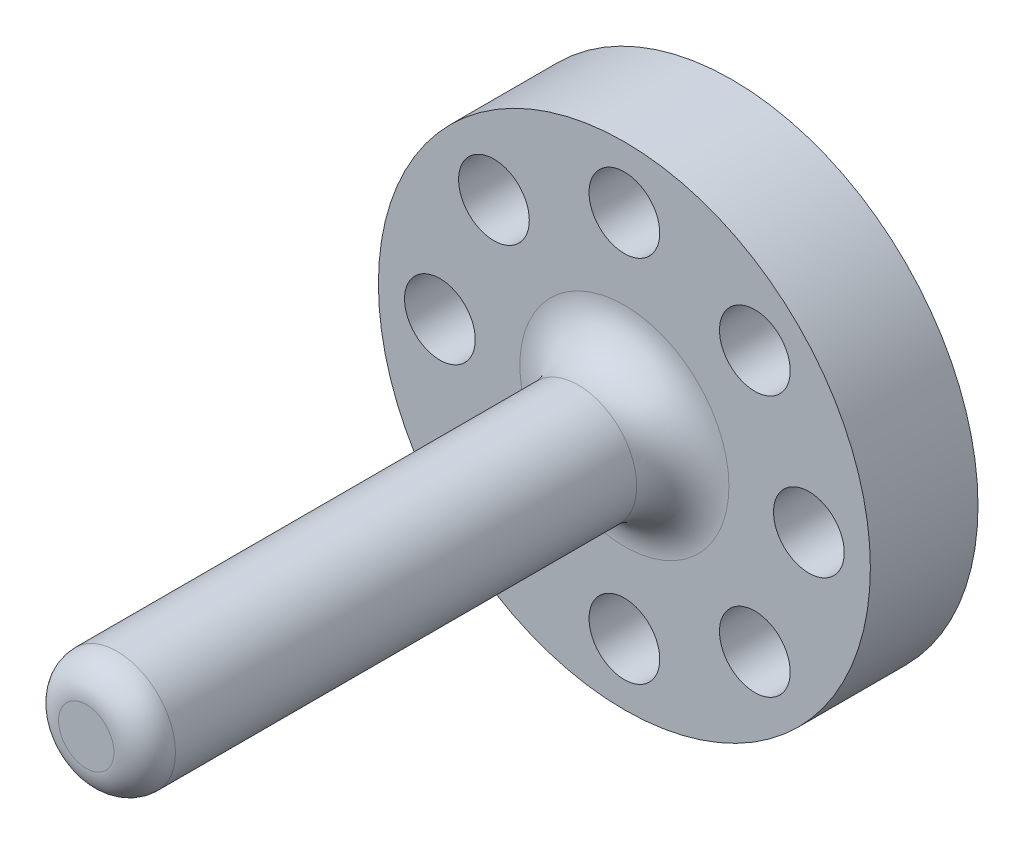
SolidWorks part; units mm, degrees
material "ABS"
ref_plane "正面" through (0, 0, 0) normal (0, 0, 1) x (1, 0, 0)
ref_plane "平面" through (0, 0, 0) normal (0, 1, 0) x (1, 0, 0)
ref_plane "右側面" through (0, 0, 0) normal (1, 0, 0) x (0, 0, -1)
sketch "ｽｹｯﾁ1" plane through (0, 0, 0) normal (0, 0, 1) x (1, 0, 0)
  circle A0 centre (0, 0) radius 8
  circle A1 centre (0, 0) radius 6 construction
  circle A2 centre (0, 6) radius 1.15
  circle A3 centre (4.2426, 4.2426) radius 1.15
  circle A4 centre (6, 0) radius 1.15
  circle A5 centre (4.2426, -4.2426) radius 1.15
  circle A6 centre (0, -6) radius 1.15
  circle A7 centre (-4.2426, -4.2426) radius 1.15
  circle A8 centre (-6, 0) radius 1.15
  circle A9 centre (-4.2426, 4.2426) radius 1.15
  circle A10 centre (0, 0) radius 4
  point P22 (0, 0)
  dimension "D1" = 12
  dimension "D2" = 16
  dimension "D3" = 2.3
  dimension "D5" = 8
  dimension "D4" = 8
extrude "ﾎﾞｽ - 押し出し1" add sketch "ｽｹｯﾁ1" along normal blind 2
sketch "ｽｹｯﾁ2" plane through (0, 0, 2) normal (0, 0, 1) x (1, 0, 0)
  circle A0 centre (0, 0) radius 8 construction
  circle A1 centre (0, 6) radius 1.15
  circle A2 centre (0, 6) radius 1.15
  circle A3 centre (4.2426, 4.2426) radius 1.15
  circle A4 centre (4.2426, 4.2426) radius 1.15
  circle A5 centre (6, 0) radius 1.15
  circle A6 centre (6, 0) radius 1.15
  circle A7 centre (4.2426, -4.2426) radius 1.15
  circle A8 centre (4.2426, -4.2426) radius 1.15
  circle A9 centre (0, -6) radius 1.15
  circle A10 centre (0, -6) radius 1.15
  circle A11 centre (-4.2426, -4.2426) radius 1.15
  circle A12 centre (-4.2426, -4.2426) radius 1.15
  circle A13 centre (-6, 0) radius 1.15
  circle A14 centre (-6, 0) radius 1.15
  circle A15 centre (-4.2426, 4.2426) radius 1.15
  circle A16 centre (-4.2426, 4.2426) radius 1.15
  circle A17 centre (0, 0) radius 8
  dimension "D1" = 0
  dimension "D2" = 0
  dimension "D3" = 0
  dimension "D4" = 0
  dimension "D5" = 0
  dimension "D6" = 0
  dimension "D7" = 0
  dimension "D8" = 0
extrude "ﾎﾞｽ - 押し出し2" add sketch "ｽｹｯﾁ2" along normal blind 1.5
sketch "ｽｹｯﾁ3" plane through (0, 0, 3.5) normal (0, 0, 1) x (1, 0, 0)
  circle A0 centre (0, 0) radius 1.9
  dimension "D1" = 3.8
extrude "ﾎﾞｽ - 押し出し3" add sketch "ｽｹｯﾁ3" along normal blind 17.5
fillet "ﾌｨﾚｯﾄ1" radius 1 1 edges at (1.9, 0, 21)
fillet "ﾌｨﾚｯﾄ2" radius 1.5 1 edges at (1.9, 0, 3.5)
